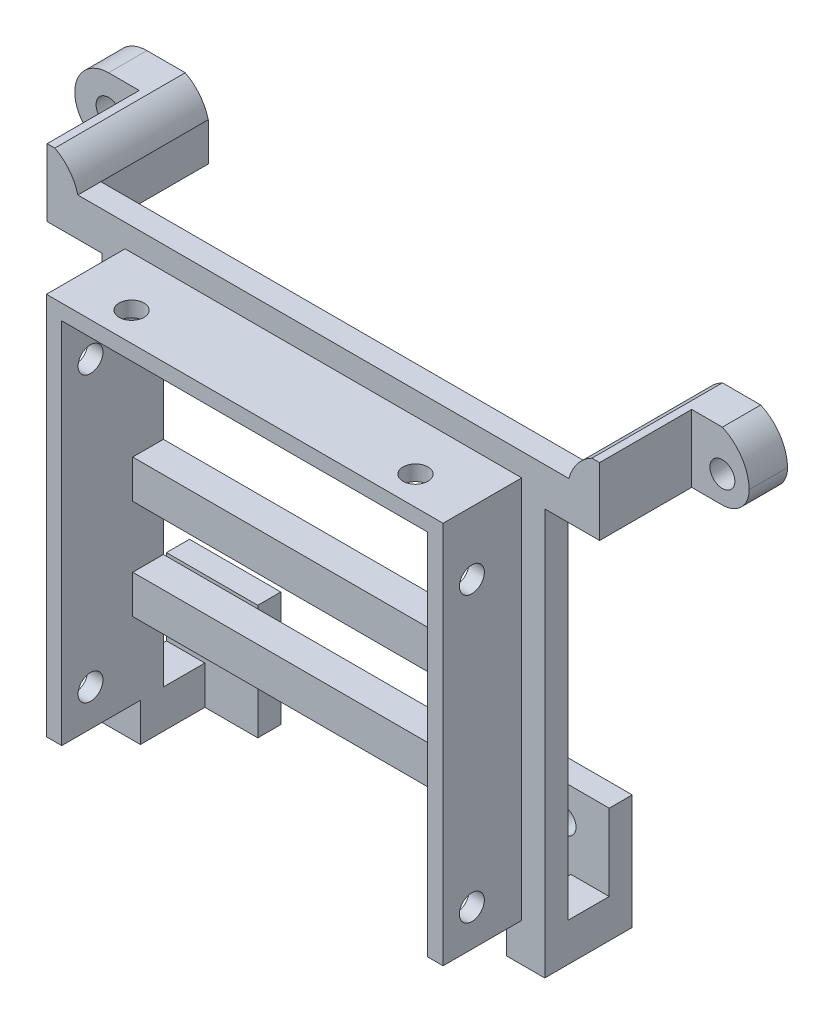
SolidWorks part; units mm, degrees
ref_plane "Alzado" through (0, 0, 0) normal (0, 0, 1) x (1, 0, 0)
ref_plane "Planta" through (0, 0, 0) normal (0, 1, 0) x (1, 0, 0)
ref_plane "Vista lateral" through (0, 0, 0) normal (1, 0, 0) x (0, 0, -1)
sketch "Croquis1" plane through (0, 0, 0) normal (0, 0, 1) x (1, 0, 0)
  line L0 (190, -61.4) -> (182, -61.4) construction
  line L7 (110, -61.4) -> (118, -61.4) construction
  line L10 (190, -61.4) -> (182, -61.4)
  line L12 (115, -52.6) -> (110, -52.6)
  line L15 (110, -61.4) -> (118, -61.4)
  line L17 (118, -61.4) -> (118, -56.4)
  line L19 (182, -61.4) -> (182, -56.4)
  line L20 (115, -52.6) -> (182, -52.6) construction
  line L22 (190, -52.6) -> (185, -52.6)
  circle A0 centre (190, -57.9) radius 1.625
  circle A1 centre (110, -57) radius 1.625
  arc A2 (118, -56.4) -> (115, -52.6) centre (112.191, -57.9018) ccw
  arc A3 (190, -61.4) -> (193.5, -57.9) centre (190, -57.9) ccw
  arc A4 (110, -52.6) -> (110, -61.4) centre (110, -57) ccw
  arc A6 (193.5, -57.9) -> (190, -52.6) centre (187.5221, -58.042) ccw
  arc A7 (185, -52.6) -> (182, -56.4) centre (187.809, -57.9018) ccw
  dimension "D1" = 3.25
  dimension "D2" = 6
  dimension "D3" = 112.191
extrude "Saliente-Extruir1" add sketch "Croquis1" along normal blind 5
sketch "Croquis4" plane through (0, 0, 5) normal (0, 0, 1) x (1, 0, 0)
  line L0 (118, -56.4) -> (114, -56.4) construction
  line L1 (115, -52.6) -> (114, -52.6)
  line L2 (115, -52.6) -> (110, -52.6) construction
  line L3 (114, -52.6) -> (114, -61.4)
  line L4 (110, -61.4) -> (118, -61.4) construction
  line L5 (114, -61.4) -> (118, -61.4)
  line L6 (118, -61.4) -> (118, -56.4)
  line L7 (182, -56.4) -> (186, -56.4) construction
  line L20 (185, -52.6) -> (186, -52.6)
  line L21 (190, -52.6) -> (185, -52.6) construction
  line L22 (186, -52.6) -> (186, -61.4)
  line L23 (182, -61.4) -> (190, -61.4) construction
  line L24 (186, -61.4) -> (182, -61.4)
  line L25 (182, -61.4) -> (182, -56.4)
  line L26 (118, -61.4) -> (118, -56.4) construction
  arc A2 (185, -52.6) -> (182, -56.4) centre (187.809, -57.9018) ccw
  arc A3 (115, -52.6) -> (118, -56.4) centre (112.191, -57.9018) cw
  dimension "D1" = 6
extrude "Saliente-Extruir2" add sketch "Croquis4" along normal blind 12
sketch "Croquis7" plane through (0, 0, 17) normal (0, 0, 1) x (1, 0, 0)
  line L0 (124.15, -70.7644) -> (121.15, -70.7644) construction
  line L1 (118, -56.4) -> (182, -56.4)
  line L2 (118, -56.4) -> (118, -61.4)
  line L4 (182, -56.4) -> (182, -61.4)
  line L5 (182, -56.4) -> (182, -61.4) construction
  line L6 (124.15, -71.3) -> (124.15, -67.6) construction
  line L7 (129.15, -61.4) -> (126.15, -61.4)
  line L8 (170.85, -61.4) -> (173.85, -61.4)
  line L14 (178.85, -61.4) -> (182, -61.4)
  line L15 (182, -61.4) -> (186, -61.4) construction
  line L20 (129.15, -61.4) -> (170.85, -61.4)
  line L25 (124.15, -109.35) -> (175.85, -109.35) construction
  line L27 (126.15, -61.4) -> (126.15, -109.35)
  line L28 (126.15, -109.35) -> (121.15, -109.35)
  line L29 (121.15, -61.4) -> (121.15, -109.35)
  line L31 (173.85, -61.4) -> (173.85, -109.35)
  line L32 (173.85, -109.35) -> (178.85, -109.35)
  line L33 (178.85, -61.4) -> (178.85, -109.35)
  line L34 (121.15, -61.4) -> (118, -61.4)
  dimension "D1" = 9.3644
  dimension "D2" = 6.15
  dimension "D3" = 47.95
extrude "Saliente-Extruir4" add sketch "Croquis7" against normal blind 3
sketch "Croquis10" plane through (0, 0, 17) normal (0, 0, 1) x (1, 0, 0)
  line L0 (124.15, -63.85) -> (124.15, -59.4) construction
  line L3 (135.2, -59.4) -> (124.15, -59.4) construction
  line L4 (175.85, -63.85) -> (175.85, -59.4) construction
  line L5 (124.15, -59.4) -> (126.15, -59.4)
  line L6 (164.8, -59.4) -> (175.85, -59.4) construction
  line L7 (124.15, -59.4) -> (124.15, -109.35)
  line L8 (124.15, -109.35) -> (126.15, -109.35)
  line L9 (126.15, -61.4) -> (126.15, -109.35)
  line L10 (175.85, -59.4) -> (173.85, -59.4)
  line L11 (175.85, -59.4) -> (175.85, -109.35)
  line L12 (175.85, -109.35) -> (173.85, -109.35)
  line L13 (173.85, -61.4) -> (173.85, -109.35)
  line L14 (126.15, -59.4) -> (173.85, -59.4)
  line L16 (126.15, -61.4) -> (173.85, -61.4)
extrude "Saliente-Extruir6" add sketch "Croquis10" along normal up to vertex (10.25 mm away)
sketch "Croquis12" plane through (124.15, 0, 0) normal (-1, 0, 0) x (0, 0, 1)
  circle A0 centre (23.5, -67.6) radius 1.625
  circle A1 centre (23.5, -104.6) radius 1.625
  dimension "D1" = 3.25
extrude "Cortar-Extruir1" cut sketch "Croquis12" against normal up to vertex (51.7 mm away) up to point (175.85, -109.35, 27.25)
sketch "Croquis13" plane through (0, -59.4, 0) normal (0, 1, 0) x (1, 0, 0)
  circle A0 centre (131.5, -23.5) radius 1.625
  circle A1 centre (168.5, -23.5) radius 1.625
  dimension "D1" = 3.25
extrude "Cortar-Extruir2" cut sketch "Croquis13" against normal up to vertex (2 mm away)
sketch "Croquis14" plane through (0, 0, 17) normal (0, 0, 1) x (1, 0, 0)
  line L0 (126.15, -109.35) -> (126.15, -114.35) construction
  line L1 (178.85, -109.35) -> (178.85, -114.35) construction
  line L2 (121.15, -109.35) -> (126.15, -109.35)
  line L3 (121.15, -109.35) -> (121.15, -114.35)
  line L4 (121.15, -114.35) -> (126.15, -114.35)
  line L5 (126.15, -109.35) -> (126.15, -114.35)
  line L7 (173.85, -109.35) -> (178.85, -109.35)
  line L8 (173.85, -109.35) -> (173.85, -114.35)
  line L9 (173.85, -114.35) -> (178.85, -114.35)
  line L10 (178.85, -109.35) -> (178.85, -114.35)
extrude "Saliente-Extruir7" add sketch "Croquis14" against normal up to vertex (11.4 mm away)
sketch "Croquis15" plane through (0, 0, 5.6) normal (0, 0, -1) x (-1, 0, 0)
  line L0 (-172.9, -103.7) -> (-178.85, -103.7) construction
  line L1 (-178.85, -114.35) -> (-166.95, -114.35)
  line L2 (-178.85, -114.35) -> (-178.85, -99.3808)
  line L3 (-178.85, -99.3808) -> (-166.95, -99.3808)
  line L4 (-166.95, -114.35) -> (-166.95, -99.3808)
  line L5 (-126.15, -114.35) -> (-126.15, -109.35) construction
  line L6 (-121.15, -114.35) -> (-133.05, -114.35)
  line L7 (-121.15, -114.35) -> (-121.15, -99.3808)
  line L8 (-121.15, -99.3808) -> (-133.05, -99.3808)
  line L9 (-133.05, -114.35) -> (-133.05, -99.3808)
  line L10 (-121.15, -114.35) -> (-126.15, -114.35) construction
  circle A0 centre (-172.9, -103.7) radius 1.625
  circle A1 centre (-127.1, -103.8) radius 1.625
  dimension "D1" = 3.25
  dimension "D2" = 6.9
  dimension "D3" = 14.9692
extrude "Saliente-Extruir8" add sketch "Croquis15" against normal blind 3
sketch "Croquis16" plane through (0, 0, 14) normal (0, 0, -1) x (-1, 0, 0)
  line L0 (-150, -61.4) -> (-150, -81.4) construction
  line L1 (-126.15, -109.35) -> (-126.15, -61.4) construction
  line L2 (-126.15, -81.4) -> (-173.85, -81.4)
  line L3 (-126.15, -81.4) -> (-126.15, -86.4)
  line L4 (-126.15, -86.4) -> (-173.85, -86.4)
  line L9 (-173.85, -81.4) -> (-173.85, -86.4)
  line L14 (-173.85, -61.4) -> (-173.85, -109.35) construction
  line L15 (-150, -86.4) -> (-150, -94.4) construction
  line L16 (-150, -94.4) -> (-173.85, -94.4) construction
  line L18 (-173.85, -94.4) -> (-126.15, -94.4)
  line L19 (-173.85, -94.4) -> (-173.85, -99.4)
  line L20 (-173.85, -99.4) -> (-126.15, -99.4)
  line L21 (-126.15, -94.4) -> (-126.15, -99.4)
  line L22 (-182, -56.4) -> (-118, -56.4) construction
  dimension "D1" = 30
extrude "Saliente-Extruir9" add sketch "Croquis16" against normal blind 4
